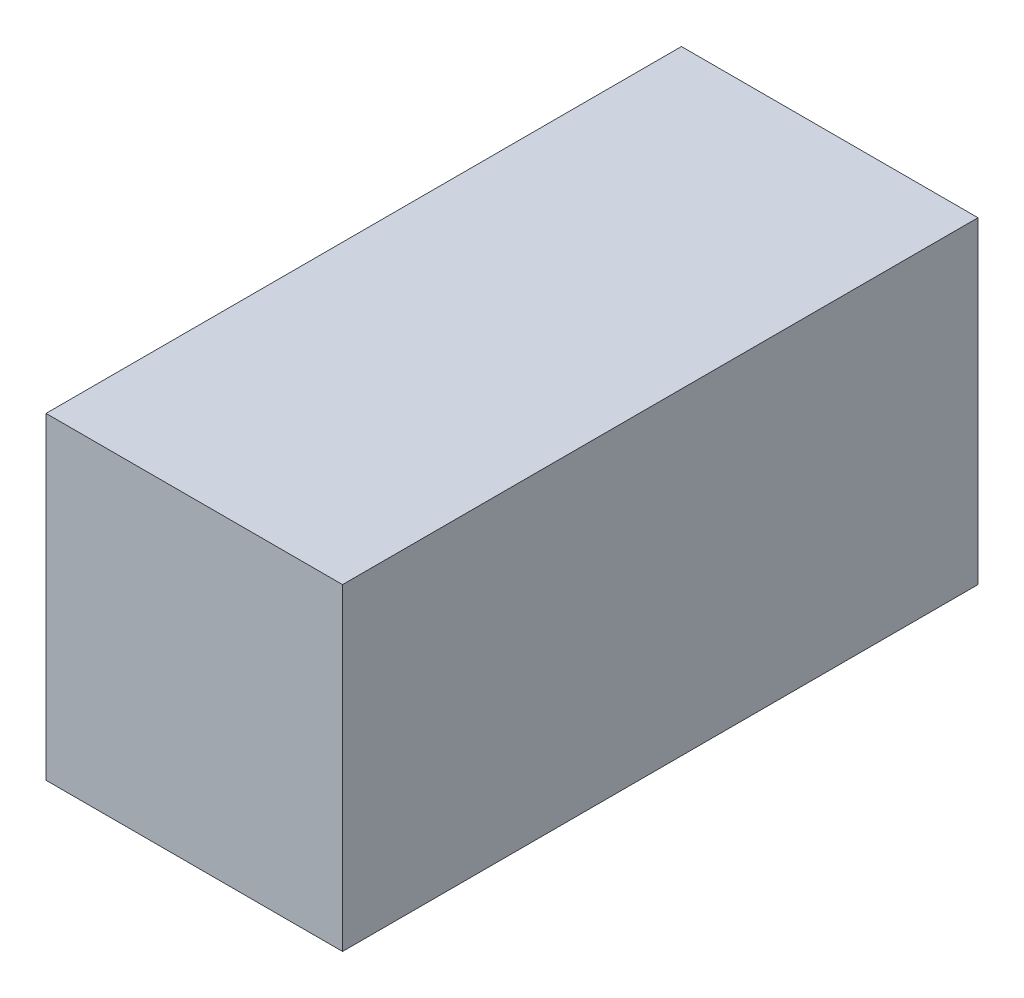
SolidWorks part; units mm, degrees
ref_plane "Front Plane" through (0, 0, 0) normal (0, 0, 1) x (1, 0, 0)
ref_plane "Top Plane" through (0, 0, 0) normal (0, 1, 0) x (1, 0, 0)
ref_plane "Right Plane" through (0, 0, 0) normal (1, 0, 0) x (0, 0, -1)
other "Configuration Table"
sketch "Sketch1" plane through (0, 0, 0) normal (0, 0, 1) x (1, 0, 0)
  line L1 (380, 405) -> (520, 405)
  line L2 (380, 405) -> (380, 555)
  line L3 (380, 555) -> (520, 555)
  line L4 (520, 405) -> (520, 555)
extrude "STORE_klape_kaset_kati_donmus_kap_3_1" add sketch "Sketch1" against normal blind 300 from offset 100 separate body
